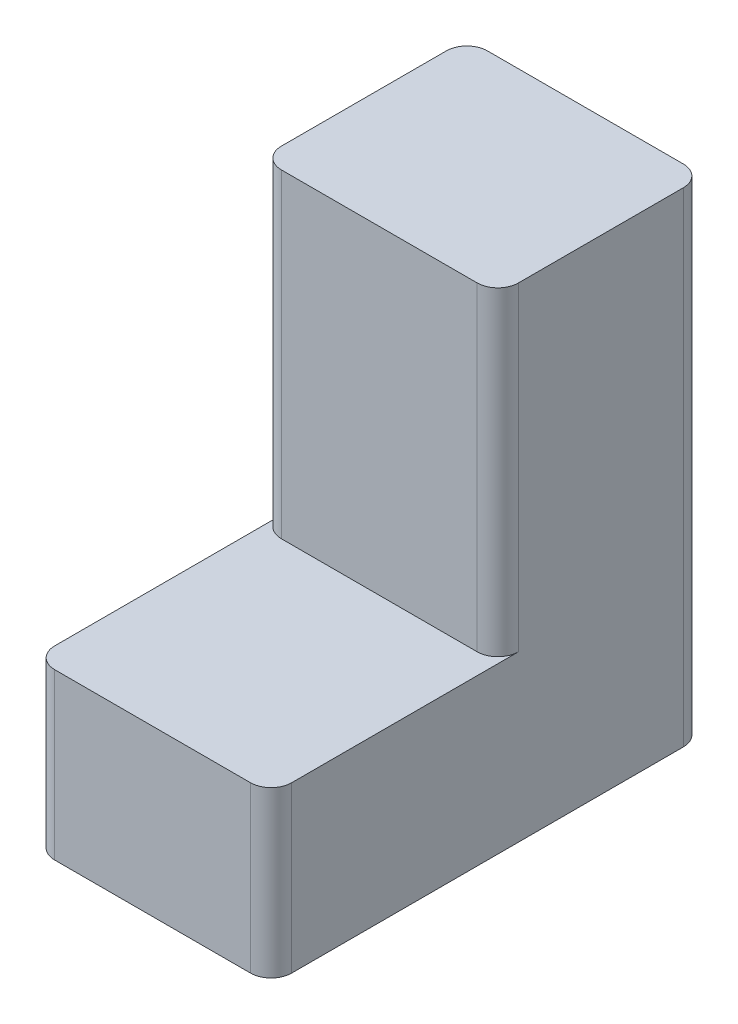
SolidWorks part; units mm, degrees
ref_plane "Front Plane" through (0, 0, 0) normal (0, 0, 1) x (1, 0, 0)
ref_plane "Top Plane" through (0, 0, 0) normal (0, 1, 0) x (1, 0, 0)
ref_plane "Right Plane" through (0, 0, 0) normal (1, 0, 0) x (0, 0, -1)
sketch "Sketch1" plane through (0, 0, 0) normal (1, 0, 0) x (0, 0, -1)
  line L0 (0, 0) -> (0, 16)
  line L1 (0, 16) -> (22, 16)
  line L2 (22, 16) -> (22, 47)
  line L3 (22, 47) -> (42, 47)
  line L4 (42, 47) -> (42, 0)
  line L5 (42, 0) -> (0, 0)
  dimension "D1" = 16
  dimension "D2" = 47
  dimension "D3" = 20
  dimension "D4" = 42
extrude "Boss-Extrude1" add sketch "Sketch1" along normal blind 23
sketch "Sketch2" plane through (0, 0, 0) normal (0, -1, 0) x (-1, 0, 0)
  line L1 (-11.5, 0) -> (-11.5, 10.5) construction
  circle A0 centre (-11.5, 10.5) radius 3.5
  dimension "D2" = 7
  dimension "D1" = 10.5
extrude "Boss-Extrude2" add sketch "Sketch2" along normal blind 6 contours A0
fillet "Fillet3" radius 2 1 edges at (23, 8, 0)
fillet "Fillet4" radius 2 1 edges at (0, 8, 0)
fillet "Fillet5" radius 2 1 edges at (23, 23.5, -42)
fillet "Fillet6" radius 2 1 edges at (0, 23.5, -42)
fillet "Fillet7" radius 2 1 edges at (0, 31.5, -22)
fillet "Fillet8" radius 2 1 edges at (23, 31.5, -22)
sketch "Sketch3" plane through (0, -6, 0) normal (0, -1, 0) x (1, 0, 0)
  line L0 (11.5, -10.5) -> (8, -10.5) construction
  line L1 (11.5, -10.5) -> (11.5, -8)
  line L2 (9.0505, -13) -> (13.9495, -13)
  line L3 (9.0505, -8) -> (13.9495, -8)
  circle A0 centre (11.5, -10.5) radius 3.5 construction
  arc A1 (13.9495, -8) -> (9.0505, -8) centre (11.5, -10.5) ccw
  arc A3 (13.9495, -13) -> (9.0505, -13) centre (11.5, -10.5) cw
  dimension "D1" = 2.5
extrude "Cut-Extrude2" cut sketch "Sketch3" against normal blind 6 contours L2 A3 | A1 L3
